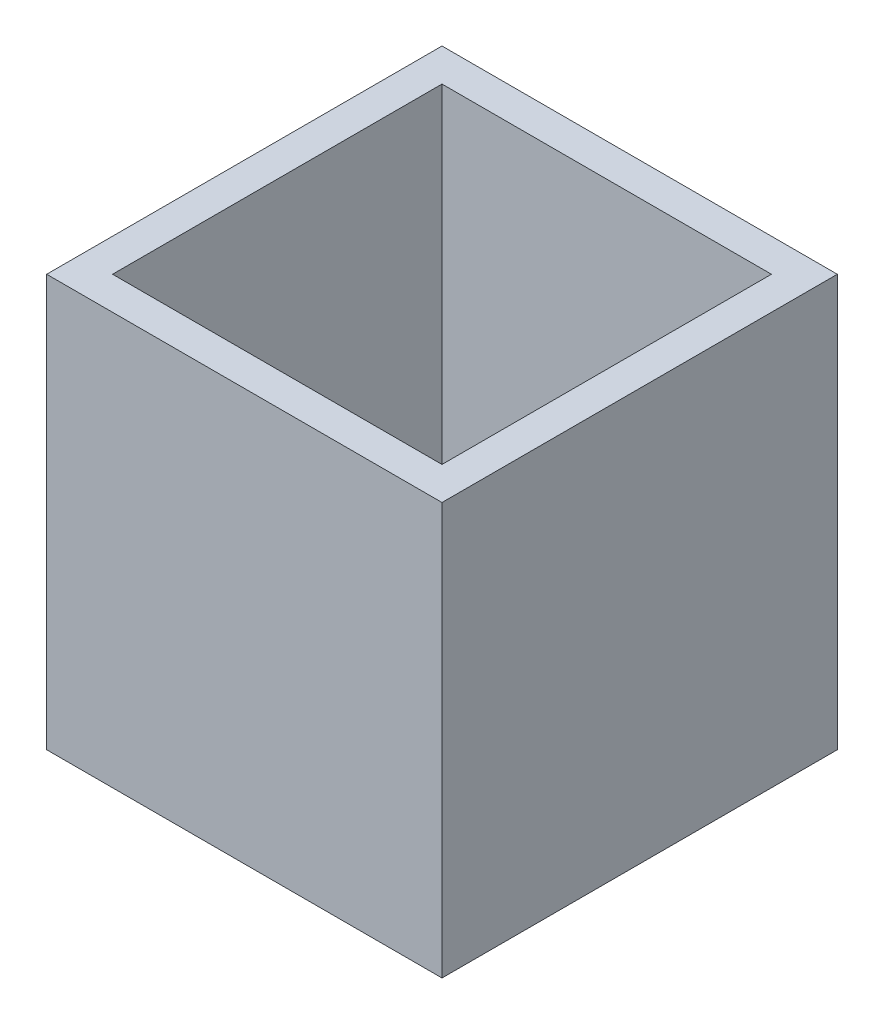
SolidWorks part; units mm, degrees
ref_plane "Front Plane" through (0, 0, 0) normal (0, 0, 1) x (1, 0, 0)
ref_plane "Top Plane" through (0, 0, 0) normal (0, 1, 0) x (1, 0, 0)
ref_plane "Right Plane" through (0, 0, 0) normal (1, 0, 0) x (0, 0, -1)
sketch "Sketch1" plane through (0, 0, 0) normal (0, 1, 0) x (1, 0, 0)
  line L1 (-2.4, -2.4) -> (2.4, -2.4)
  line L2 (-2.4, -2.4) -> (-2.4, 2.4)
  line L3 (-2.4, 2.4) -> (2.4, 2.4)
  line L4 (2.4, -2.4) -> (2.4, 2.4)
  line L5 (-2.4, -2.4) -> (2.4, 2.4) construction
  line L6 (-2.4, 2.4) -> (2.4, -2.4) construction
  line L7 (-2, -2) -> (2, -2)
  line L8 (-2, -2) -> (-2, 2)
  line L9 (-2, 2) -> (2, 2)
  line L10 (2, -2) -> (2, 2)
  line L11 (-2, -2) -> (2, 2) construction
  line L12 (-2, 2) -> (2, -2) construction
  point P0 (0, 0)
  point P6 (0, 0)
  dimension "D1" = 4.8
  dimension "D2" = 4.8
  dimension "D3" = 4
  dimension "D4" = 4
extrude "Boss-Extrude1" add sketch "Sketch1" along normal blind 5
